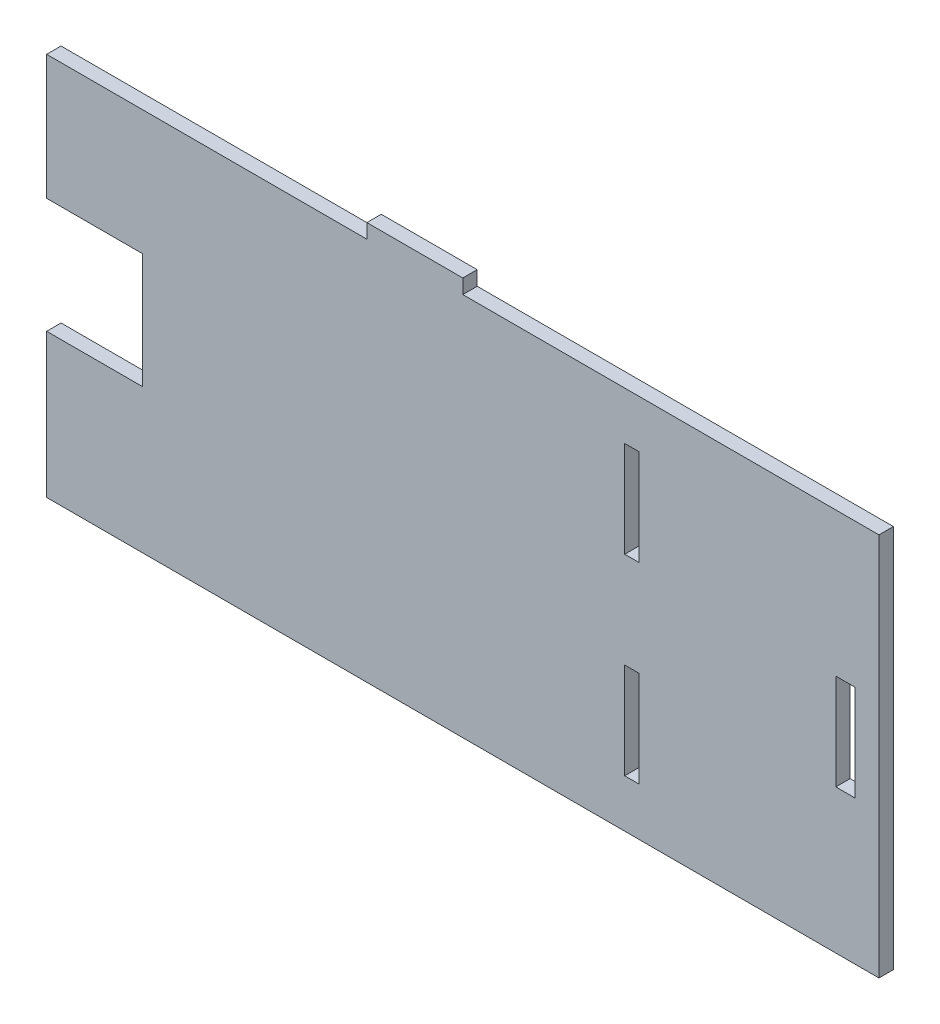
SolidWorks part; units mm, degrees
ref_plane "Plan de face" through (0, 0, 0) normal (0, 0, 1) x (1, 0, 0)
ref_plane "Plan de dessus" through (0, 0, 0) normal (0, 1, 0) x (1, 0, 0)
ref_plane "Plan de droite" through (0, 0, 0) normal (1, 0, 0) x (0, 0, -1)
sketch "Esquisse2" plane through (0, 0, 0) normal (0, 0, 1) x (1, 0, 0)
  line L1 (0, 0) -> (-173.5, 0)
  line L2 (0, 0) -> (0, -80)
  line L3 (0, -80) -> (-173.5, -80)
  line L4 (-173.5, 0) -> (-173.5, -80)
  dimension "D1" = 173.5
  dimension "D2" = 80
extrude "Boss.-Extru.2" add sketch "Esquisse2" along normal blind 3
sketch "Esquisse3" plane through (0, 0, 3) normal (0, 0, 1) x (1, 0, 0)
  line L0 (-53, -70) -> (-50, -70)
  line L1 (-53, -30) -> (-50, -30)
  line L2 (-53, -30) -> (-53, -10)
  line L3 (-53, -10) -> (-50, -10)
  line L4 (-50, -30) -> (-50, -10)
  line L5 (-53, -70) -> (-53, -50)
  line L6 (-53, -50) -> (-50, -50)
  line L7 (-50, -70) -> (-50, -50)
  line L8 (0, 0) -> (-173.5, 0) construction
  line L9 (0, -80) -> (0, 0) construction
  dimension "D1" = 3
  dimension "D2" = 20
  dimension "D3" = 20
  dimension "D4" = 20
  dimension "D5" = 3
  dimension "D6" = 10
  dimension "D7" = 50
extrude "Enlèv. mat.-Extru.1" cut sketch "Esquisse3" against normal up to next
sketch "Esquisse4" plane through (0, 0, 0) normal (0, 1, 0) x (1, 0, 0)
  line L0 (0, -3) -> (-86.75, -3) construction
  line L2 (0, -3) -> (-173.5, -3) construction
  line L3 (0, 0) -> (-173.5, 0) construction
  line L4 (-86.75, -3) -> (-106.75, -3)
  line L5 (-86.75, -3) -> (-86.75, 0)
  line L6 (-86.75, 0) -> (-106.75, 0)
  line L7 (-106.75, -3) -> (-106.75, 0)
  dimension "D1" = 20
extrude "Boss.-Extru.3" add sketch "Esquisse4" along normal blind 3
sketch "Esquisse5" plane through (0, 0, 0) normal (0, 0, -1) x (-1, 0, 0)
  line L0 (0, -80) -> (0, 0) construction
  line L1 (5, -30) -> (9, -30)
  line L2 (5, -30) -> (5, -50)
  line L3 (5, -50) -> (9, -50)
  line L4 (9, -30) -> (9, -50)
  line L5 (0, 0) -> (86.75, 0) construction
  dimension "D1" = 5
  dimension "D2" = 30
  dimension "D3" = 20
  dimension "D4" = 4
extrude "Enlèv. mat.-Extru.2" cut sketch "Esquisse5" against normal blind 10
sketch "Esquisse6" plane through (0, 0, 3) normal (0, 0, 1) x (1, 0, 0)
  line L0 (-173.5, 0) -> (-173.5, -80) construction
  line L1 (-173.5, -26) -> (-153.5, -26)
  line L2 (-173.5, -26) -> (-173.5, -50)
  line L3 (-173.5, -50) -> (-153.5, -50)
  line L4 (-153.5, -26) -> (-153.5, -50)
  line L5 (-106.75, 0) -> (-173.5, 0) construction
  dimension "D1" = 20
  dimension "D2" = 24
  dimension "D3" = 26
extrude "Enlèv. mat.-Extru.3" cut sketch "Esquisse6" against normal blind 10
